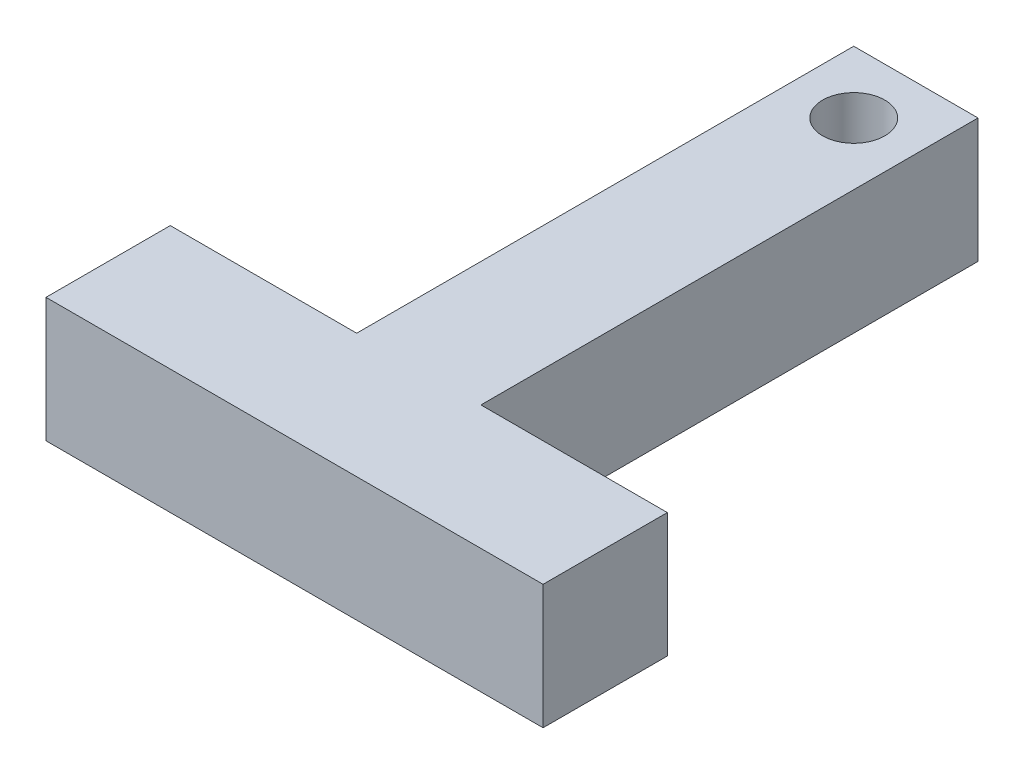
SolidWorks part; units mm, degrees
ref_plane "前视基准面" through (0, 0, 0) normal (0, 0, 1) x (1, 0, 0)
ref_plane "上视基准面" through (0, 0, 0) normal (0, 1, 0) x (1, 0, 0)
ref_plane "右视基准面" through (0, 0, 0) normal (1, 0, 0) x (0, 0, -1)
sketch "草图1" plane through (0, 0, 0) normal (0, 1, 0) x (1, 0, 0)
  line L0 (0, -55) -> (0, 55) construction
  line L1 (-2, 35.7707) -> (-0.5, 35.7707)
  line L2 (-2, 35.7707) -> (-2, 34.7707)
  line L3 (-2, 34.7707) -> (2, 34.7707)
  line L4 (2, 35.7707) -> (2, 34.7707)
  line L5 (0, 35.2707) -> (0, 40.3351) construction
  line L7 (0, 0) -> (0, 35.2707) construction
  line L9 (-0.5, 39.7707) -> (0.5, 39.7707)
  line L10 (-0.5, 39.7707) -> (-0.5, 35.7707)
  line L12 (0.5, 39.7707) -> (0.5, 35.7707)
  line L15 (0.5, 35.7707) -> (2, 35.7707)
  point P0 (0, 35.2707)
  point P10 (0, 37.1477)
  dimension "D1" = 4
  dimension "D2" = 1
  dimension "D3" = 1
  dimension "D4" = 1.5
  dimension "D5" = 4
extrude "凸台-拉伸1" add sketch "草图1" along normal blind 1
sketch "草图2" plane through (0, 1, 0) normal (0, 1, 0) x (1, 0, 0)
  line L0 (0.5, 39.7707) -> (-0.5, 39.7707) construction
  line L2 (-0.5, 39.7707) -> (-0.5, 35.7707) construction
  circle A0 centre (0, 39.2707) radius 0.25
  point P6 (-0.5, 39.3525)
  dimension "D3" = 0.5
  dimension "D1" = 0.5
  dimension "D2" = 0.5
extrude "切除-拉伸1" cut sketch "草图2" against normal through all
